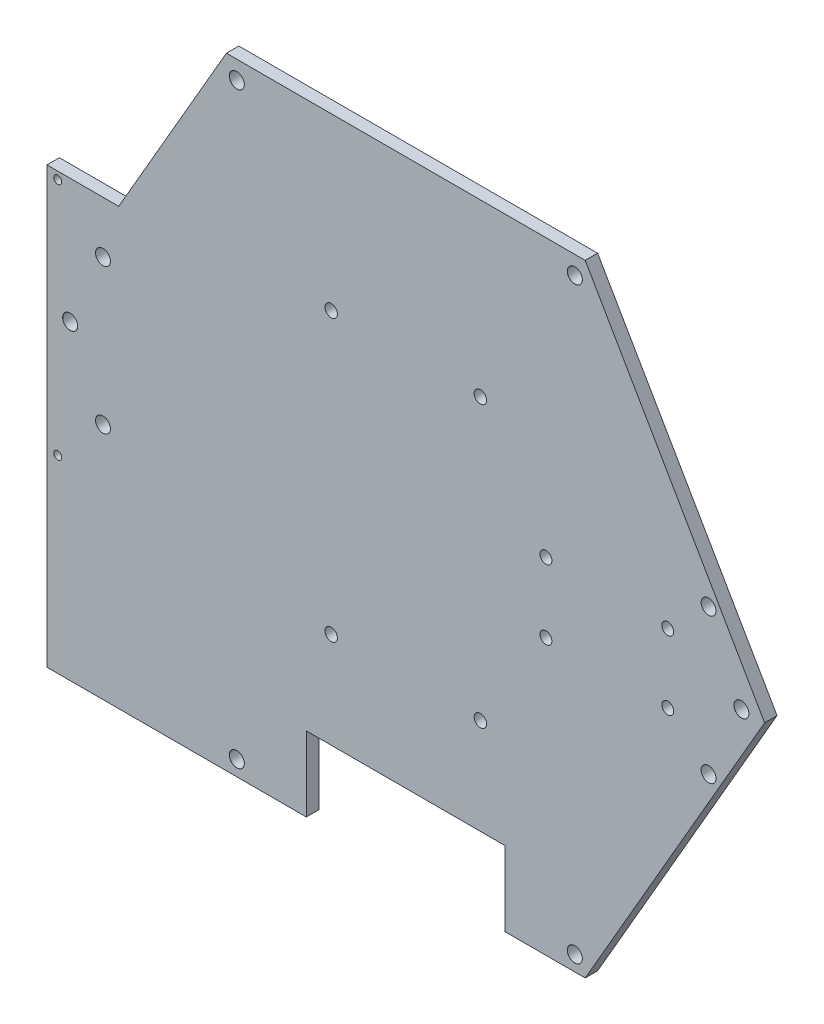
SolidWorks part; units mm, degrees
ref_plane "前视基准面" through (0, 0, 0) normal (0, 0, 1) x (1, 0, 0)
ref_plane "上视基准面" through (0, 0, 0) normal (0, 1, 0) x (1, 0, 0)
ref_plane "右视基准面" through (0, 0, 0) normal (1, 0, 0) x (0, 0, -1)
other "Configuration Table"
sketch "草图8" plane through (0, 0, 0) normal (0, 0, 1) x (1, 0, 0)
  line L0 (0, -95) -> (0, 125) construction
  line L1 (144.3376, 0) -> (72.1688, 125)
  line L2 (72.1688, 125) -> (-72.1688, 125)
  line L3 (-72.1688, 125) -> (-144.3376, 0)
  line L4 (-144.3376, 0) -> (-72.1688, -125)
  line L5 (-72.1688, -125) -> (-40, -125)
  line L6 (72.1688, -125) -> (144.3376, 0)
  line L7 (0, 125) -> (0, -95) construction
  line L8 (-40, -125) -> (-40, -95)
  line L9 (-40, -95) -> (40, -95)
  line L10 (40, -125) -> (40, -95)
  line L11 (40, -125) -> (72.1688, -125)
  arc A0 (40, -118.4272) -> (-40, -118.4272) centre (0, 0) ccw construction
  point P15 (0, -95)
  dimension "D1" = 250
  dimension "D2" = 40
  dimension "D3" = 30
extrude "凸台-拉伸3" add sketch "草图8" along normal blind 5
sketch "草图19" plane through (0, 0, 5) normal (0, 0, 1) x (1, 0, 0)
  point P0 (-135.0031, 0)
  point P2 (-67.9807, -118.8668)
  point P4 (-67.9807, 117.662)
hole_wizard "Ø6.0 (6) 直径孔1" positions "草图19" profile "草图18" hole size "Ø6.0" standard "GB" end condition through all
sketch "草图18" plane through (-135.0031, 0, 5) normal (1, 0, 0) x (0, -1, 0)
  line L0 (0, 0) -> (0, 5)
  line L1 (0, 5) -> (3, 5)
  line L2 (3, 5) -> (3, 0.025)
  line L3 (3, 0.025) -> (3.025, 0)
  line L5 (3.025, 0) -> (0, 0)
  line L6 (-3, 0.025) -> (-3.025, 0) construction
  line L11 (0, -6.35) -> (0, 107.95) construction
  dimension "通孔孔直径" = 6
  dimension "通孔孔深度" = 5
  dimension "近端锥形沉头孔直径" = 6.05
  dimension "近端锥形沉头孔角度" = 90
mirror "镜向2" about plane through (0, 0, 0) normal (1, 0, 0) of "Ø6.0 (6) 直径孔1"
sketch "草图20" plane through (0, 0, 5) normal (0, 0, 1) x (1, 0, 0)
  circle A0 centre (56.3709, 13.653) radius 2.4
  circle A1 centre (105.3709, 13.3246) radius 2.4
  circle A2 centre (56.3709, -14.347) radius 2.4
  circle A3 centre (105.3709, -14.347) radius 2.4
  dimension "D1" = 4.8
  dimension "D2" = 28
  dimension "D3" = 49
extrude "切除-拉伸2" cut sketch "草图20" against normal through all
sketch "草图32" plane through (0, 0, 0) normal (0, 0, 1) x (1, 0, 0)
  line L0 (0, 125) -> (0, -96.202) construction
  line L1 (72.1688, 125) -> (-72.1688, 125) construction
sketch "草图33" plane through (0, 0, 5) normal (0, 0, 1) x (1, 0, 0)
  line L0 (0, 125) -> (0, -95) construction
  line L1 (-40, -95) -> (40, -95) construction
  line L2 (-144.3376, 0) -> (144.3376, 0) construction
  circle A0 centre (-121.7978, -29.1812) radius 3
  circle A1 centre (121.7978, -29.1812) radius 3
  circle A2 centre (121.7978, 29.1812) radius 3
  circle A3 centre (-121.7978, 29.1812) radius 3
extrude "切除-拉伸3" cut sketch "草图33" against normal through all
sketch "草图34" plane through (0, 0, 5) normal (0, 0, 1) x (1, 0, 0)
  line L0 (0, 125) -> (0, -96.202) construction
  line L1 (-144.3376, 0) -> (144.3376, 0) construction
  circle A0 centre (-30, -56.3924) radius 2.5
  circle A1 centre (30, -56.3924) radius 2.5
  circle A2 centre (30, 56.3924) radius 2.5
  circle A3 centre (-30, 56.3924) radius 2.5
extrude "切除-拉伸4" cut sketch "草图34" against normal through all
sketch "草图35" plane through (0, 0, 0) normal (0, 0, 1) x (1, 0, 0)
  line L0 (-115.4701, 50) -> (-144.3376, 50)
  line L1 (-72.1688, 125) -> (-144.3376, 0) construction
  line L2 (-144.3376, 50) -> (-144.3376, -125)
  line L3 (-144.3376, -125) -> (-72.1688, -125)
  line L4 (-72.1688, -125) -> (-144.3376, 0)
  line L5 (-144.3376, 0) -> (-115.4701, 50)
  circle A0 centre (-140, 47) radius 1.6
  circle A1 centre (-140, -49) radius 1.6
  dimension "D1" = 50
  dimension "D2" = 0
extrude "凸台-拉伸5" add sketch "草图35" along normal blind 5 contours L2 L5 L0 A0 | L3 L4 L2 A1
